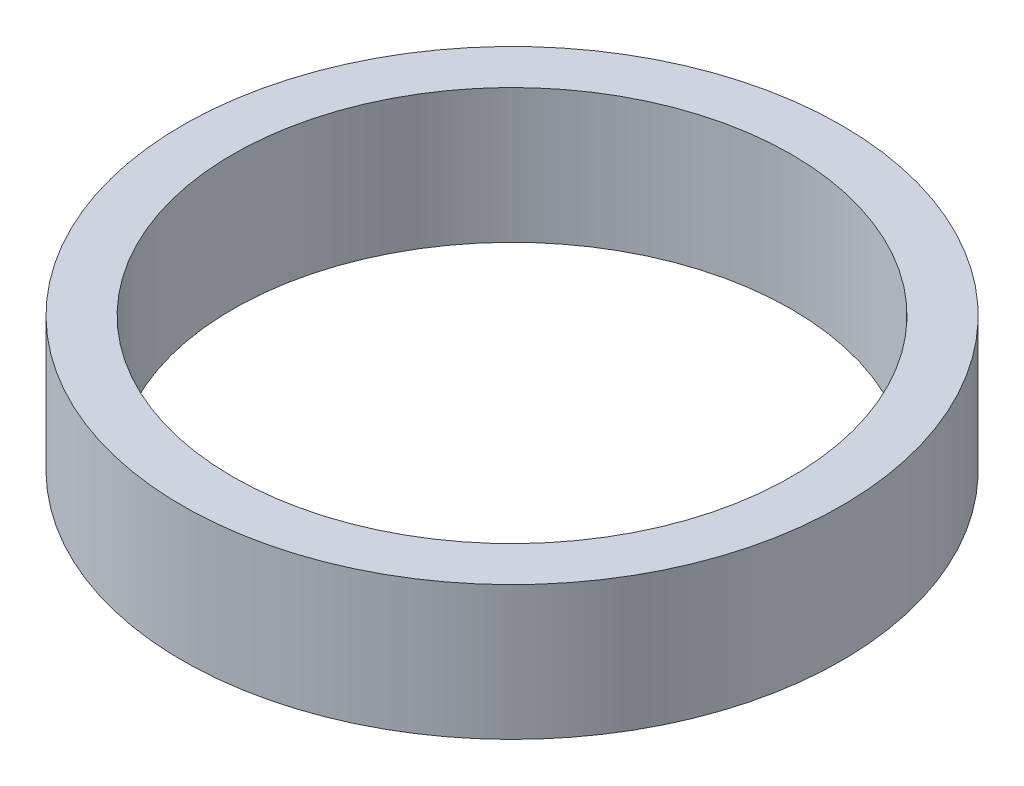
SolidWorks part; units mm, degrees
ref_plane "Спереди" through (0, 0, 0) normal (0, 0, 1) x (1, 0, 0)
ref_plane "Сверху" through (0, 0, 0) normal (0, 1, 0) x (1, 0, 0)
ref_plane "Справа" through (0, 0, 0) normal (1, 0, 0) x (0, 0, -1)
sketch "Эскиз1" plane through (0, 0, 0) normal (0, 0, 1) x (1, 0, 0)
  line L0 (0, 0) -> (0, 13983.1794) construction
  line L6 (-29.5, 12) -> (-25, 12)
  line L7 (-29.5, 12) -> (-29.5, 0)
  line L8 (-29.5, 0) -> (-25, 0)
  line L9 (-25, 12) -> (-25, 0)
  dimension "D1" = 50
  dimension "D2" = 12
  dimension "D3" = 59
revolve "Повернуть1" add sketch "Эскиз1" angle 360 about L0
